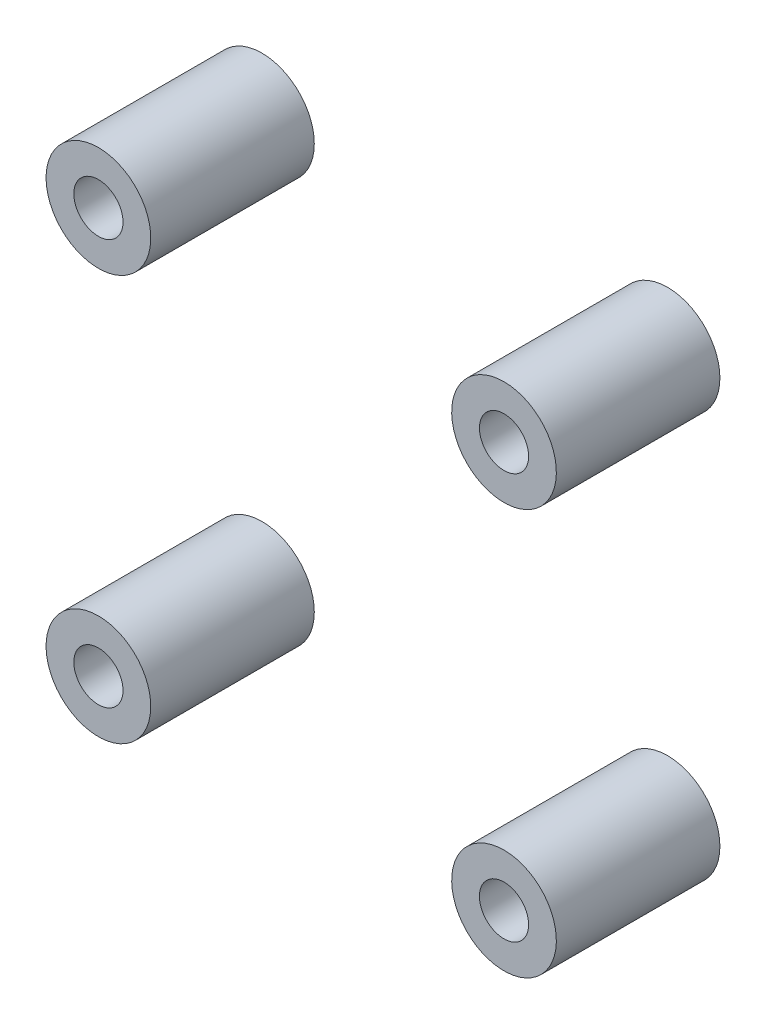
SolidWorks part; units mm, degrees
ref_plane "前视基准面" through (0, 0, 0) normal (0, 0, 1) x (1, 0, 0)
ref_plane "上视基准面" through (0, 0, 0) normal (0, 1, 0) x (1, 0, 0)
ref_plane "右视基准面" through (0, 0, 0) normal (1, 0, 0) x (0, 0, -1)
sketch "草图1" plane through (0, 0, 0) normal (0, 0, 1) x (1, 0, 0)
  circle A8 centre (15.5, 15.5) radius 1.88
  circle A9 centre (15.5, 15.5) radius 4
  circle A10 centre (15.5, -15.5) radius 4
  circle A11 centre (-15.5, -15.5) radius 4
  circle A12 centre (-15.5, 15.5) radius 4
  circle A13 centre (0, 0) radius 6.7448 construction
  circle A14 centre (15.5, -15.5) radius 1.88
  circle A15 centre (-15.5, -15.5) radius 1.88
  circle A16 centre (-15.5, 15.5) radius 1.88
  point P11 (0, 0)
  point P22 (0, 0)
  dimension "D1" = 3.76
  dimension "D2" = 8
  dimension "D4" = 4
  dimension "D3" = 4
extrude "凸台-拉伸1" add sketch "草图1" along normal up to surface (12.5 mm away)
